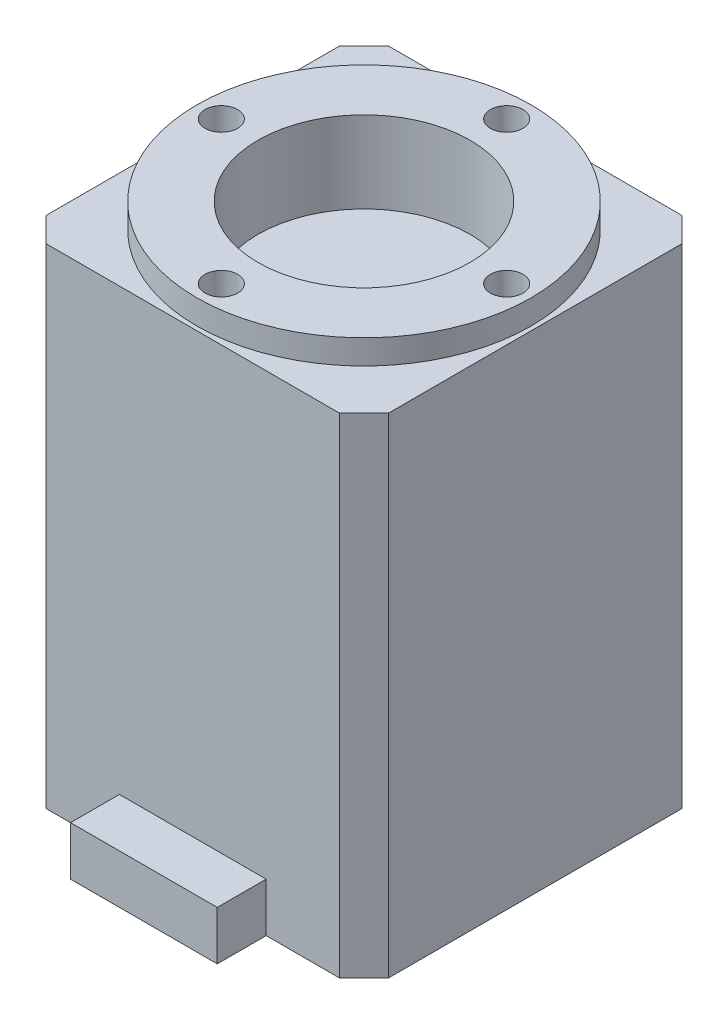
SolidWorks part; units mm, degrees
material "Plain Carbon Steel"
ref_plane "Front Plane" through (0, 0, 0) normal (0, 0, 1) x (1, 0, 0)
ref_plane "Top Plane" through (0, 0, 0) normal (0, 1, 0) x (1, 0, 0)
ref_plane "Right Plane" through (0, 0, 0) normal (1, 0, 0) x (0, 0, -1)
sketch "Esquisse1" plane through (0, 0, 0) normal (0, 1, 0) x (1, 0, 0)
  line L9 (0, 0) -> (42, 0)
  line L10 (0, 0) -> (0, 42)
  line L11 (0, 42) -> (42, 42)
  line L12 (42, 0) -> (42, 42)
  dimension "D1" = 42
extrude "Boss.-Extru.1" add sketch "Esquisse1" along normal blind 60
sketch "Esquisse2" plane through (0, 60, 0) normal (0, 1, 0) x (1, 0, 0)
  line L0 (42, 42) -> (0, 0) construction
  circle A0 centre (21, 21) radius 20.5
  dimension "D1" = 41
extrude "Boss.-Extru.2" add sketch "Esquisse2" along normal blind 3
sketch "Esquisse3" plane through (0, 63, 0) normal (0, 1, 0) x (1, 0, 0)
  circle A0 centre (21, 21) radius 13
  circle A1 centre (21, 21) radius 20.5 construction
  dimension "D1" = 26
extrude "Enlèv. mat.-Extru.1" cut sketch "Esquisse3" against normal blind 10
sketch "Esquisse4" plane through (0, 63, 0) normal (0, 1, 0) x (1, 0, 0)
  line L0 (3.5, 21) -> (38.5, 21) construction
  line L1 (21, 38.5) -> (21, 3.5) construction
  circle A0 centre (3.5, 21) radius 2
  circle A1 centre (21, 38.5) radius 2
  circle A2 centre (38.5, 21) radius 2
  circle A3 centre (21, 3.5) radius 2
  circle A4 centre (21, 21) radius 17.5 construction
  circle A5 centre (21, 21) radius 20.5 construction
  point P15 (21, 21)
  dimension "D1" = 4
  dimension "D2" = 35
extrude "Enlèv. mat.-Extru.2" cut sketch "Esquisse4" against normal blind 3.5
chamfer "Chanfrein1" distance 3 angle 45 4 edges at (42, 30, -42) (42, 30, 0) (0, 30, -42) (0, 30, 0)
sketch "Esquisse5" plane through (0, 0, 0) normal (0, 0, 1) x (1, 0, 0)
  line L0 (3, 0) -> (39, 0) construction
  line L1 (12, 6) -> (30, 6)
  line L2 (12, 6) -> (12, 0)
  line L3 (12, 0) -> (30, 0)
  line L4 (30, 6) -> (30, 0)
  line L5 (21.1535, 6) -> (21, 0) construction
  dimension "D1" = 6
  dimension "D2" = 18
extrude "Boss.-Extru.3" add sketch "Esquisse5" along normal blind 6
